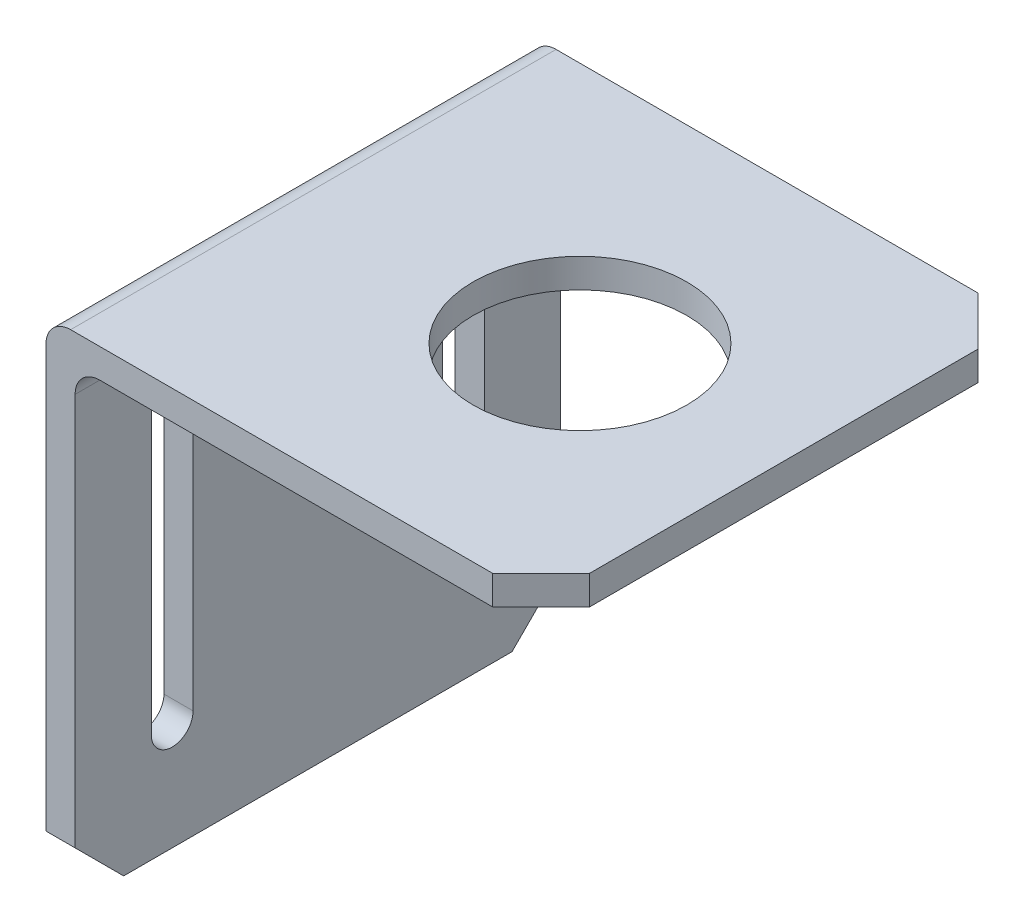
SolidWorks part; units mm, degrees
material "ASTM A36 Steel"
ref_plane "Front Plane" through (0, 0, 0) normal (0, 0, 1) x (1, 0, 0)
ref_plane "Top Plane" through (0, 0, 0) normal (0, 1, 0) x (1, 0, 0)
ref_plane "Right Plane" through (0, 0, 0) normal (1, 0, 0) x (0, 0, -1)
sketch "Sketch1" plane through (0, 0, 0) normal (0, 0, 1) x (1, 0, 0)
  line L0 (-58.9314, -35.7221) -> (-55.9314, -35.7221)
  line L5 (-55.9314, -35.7221) -> (-55.9314, 12.2779)
  line L6 (-55.9314, 12.2779) -> (-7.9314, 12.2779)
  line L7 (-7.9314, 12.2779) -> (-7.9314, 15.2779)
  line L8 (-7.9314, 15.2779) -> (-58.9314, 15.2779)
  line L9 (-58.9314, 15.2779) -> (-58.9314, -35.7221)
  dimension "D1" = 51
  dimension "D2" = 51
  dimension "D3" = 3
  dimension "D4" = 3
extrude "Boss-Extrude1" add sketch "Sketch1" along normal blind 50
chamfer "Chamfer1" distance 5 angle 45 4 edges at (-57.4314, -35.7221, 50) (-57.4314, -35.7221, 0) (-7.9314, 13.7779, 0) (-7.9314, 13.7779, 50)
fillet "Fillet1" radius 2.54 2 edges at (-55.9314, 12.2779, 25) (-58.9314, 15.2779, 25)
sketch "Sketch3" plane through (-55.9314, 0, 0) normal (1, 0, 0) x (0, 0, -1)
  line L0 (-40, 5.1279) -> (-40, -24.5721) construction
  line L1 (-37.85, 5.1279) -> (-37.85, -24.5721)
  line L2 (-42.15, 5.1279) -> (-42.15, -24.5721)
  line L3 (-45, -35.7221) -> (-5, -35.7221) construction
  line L4 (-50, -30.7221) -> (-50, 9.7379) construction
  line L5 (-53.5339, -26.7221) -> (-20.882, -26.7221) construction
  line L6 (-45, -35.7221) -> (-5, -35.7221) construction
  line L7 (-48.0127, 7.2779) -> (-15.3609, 7.2779) construction
  line L8 (-25, -1035.7221) -> (-25, 48964.2779) construction
  line L9 (-10, 5.1279) -> (-10, -24.5721) construction
  line L10 (-12.15, 5.1279) -> (-12.15, -24.5721)
  line L11 (-7.85, 5.1279) -> (-7.85, -24.5721)
  line L12 (0, 15.2779) -> (-50, 15.2779) construction
  line L13 (-45, -35.7221) -> (-5, -35.7221) construction
  arc A0 (-37.85, 5.1279) -> (-42.15, 5.1279) centre (-40, 5.1279) ccw
  arc A1 (-42.15, -24.5721) -> (-37.85, -24.5721) centre (-40, -24.5721) ccw
  arc A2 (-12.15, 5.1279) -> (-7.85, 5.1279) centre (-10, 5.1279) cw
  arc A3 (-7.85, -24.5721) -> (-12.15, -24.5721) centre (-10, -24.5721) cw
  point P2 (-40, -9.7221)
  point P18 (-25, -35.7221)
  point P20 (-10, -9.7221)
  dimension "D1" = 10
  dimension "D2" = 9
  dimension "D3" = 34
extrude "Cut-Extrude1" cut sketch "Sketch3" against normal blind 50
sketch "Sketch4" plane through (0, 15.2779, 0) normal (0, 1, 0) x (1, 0, 0)
  line L0 (-7.9314, -45) -> (-7.9314, -5) construction
  circle A0 centre (-28.9314, -25) radius 11
  point P5 (-7.9314, -25)
  dimension "D2" = 22
  dimension "D1" = 21
extrude "Cut-Extrude2" cut sketch "Sketch4" against normal up to surface (3 mm away) up to face at (-24.7514, 12.2779, 25)
